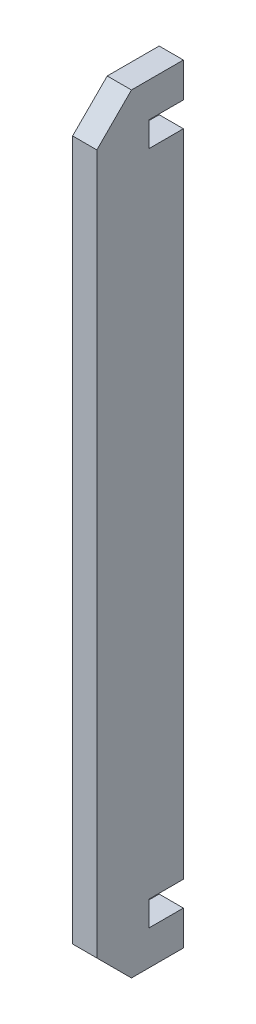
SolidWorks part; units mm, degrees
ref_plane "Front Plane" through (0, 0, 0) normal (1, 0, 0) x (0, 1, 0)
ref_plane "Top Plane" through (0, 0, 0) normal (0, 0, 1) x (0, 1, 0)
ref_plane "Right Plane" through (0, 0, 0) normal (0, 1, 0) x (-1, 0, 0)
sketch "Sketch1" plane through (0, 0, 0) normal (1, 0, 0) x (0, 1, 0)
  line L0 (-17.9216, 5.2239) -> (75.9784, 5.2239)
  line L1 (-26.5216, 0.2239) -> (84.5784, 0.2239)
  line L2 (-26.5216, 0.2239) -> (-26.5216, 12.7239)
  line L3 (-26.5216, 12.7239) -> (84.5784, 12.7239)
  line L4 (84.5784, 0.2239) -> (84.5784, 12.7239)
  line L5 (-21.5216, 0.2239) -> (-17.9216, 0.2239)
  line L6 (-21.5216, 0.2239) -> (-21.5216, 5.2239)
  line L7 (-21.5216, 5.2239) -> (-17.9216, 5.2239)
  line L8 (-17.9216, 0.2239) -> (-17.9216, 5.2239)
  line L9 (75.9784, 0.2239) -> (79.5784, 0.2239)
  line L10 (75.9784, 0.2239) -> (75.9784, 5.2239)
  line L11 (75.9784, 5.2239) -> (79.5784, 5.2239)
  line L12 (79.5784, 0.2239) -> (79.5784, 5.2239)
  line L13 (29.0284, 5.2239) -> (29.0284, 0.2239)
  dimension "D1" = 12.5
  dimension "D2" = 3.6
  dimension "D3" = 3.6
  dimension "D4" = 93.9
  dimension "D5" = 5
  dimension "D6" = 5
  dimension "D7" = 111.1
extrude "Boss-Extrude1" add sketch "Sketch1" along normal blind 3.5 contours L12 L1 L4 L3 L2 L6 L7 L0 L11 | L13 L0 L8 L1 | L0 L13 L1 L10
chamfer "Chamfer1" distance 5 angle 45 2 edges at (1.75, 84.5784, 12.7239) (1.75, -26.5216, 12.7239)
